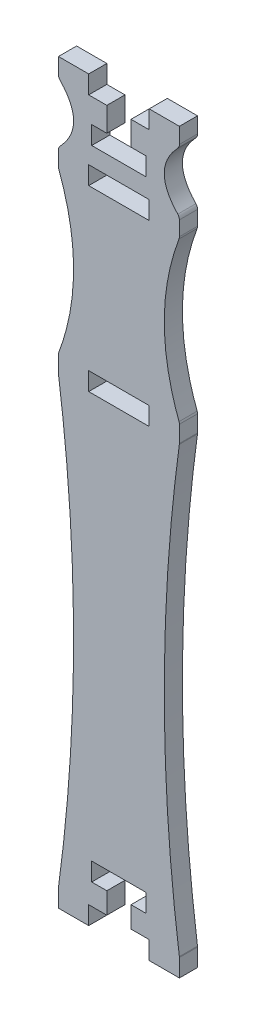
SolidWorks part; units mm, degrees
ref_plane "Alzado" through (0, 0, 0) normal (0, 0, 1) x (1, 0, 0)
ref_plane "Planta" through (0, 0, 0) normal (0, 1, 0) x (1, 0, 0)
ref_plane "Vista lateral" through (0, 0, 0) normal (1, 0, 0) x (0, 0, -1)
sketch "Croquis1" plane through (0, 0, 0) normal (0, 0, 1) x (1, 0, 0)
  line L1 (-10, 70) -> (-10, 67)
  line L2 (-7, 67) -> (-10, 67)
  line L4 (-15, 70) -> (-15, 67.4057)
  line L6 (-7, -45.5) -> (-7, -49)
  line L7 (-0.5, -42.5) -> (-9.5, -42.5)
  line L9 (-10, 70) -> (-15, 70)
  line L10 (-9.5, 60) -> (-0.5, 60)
  line L11 (-10, -52) -> (-10, -49)
  line L12 (-10, -52) -> (-15, -52)
  line L13 (-0.5, -42.5) -> (-0.5, -45.5)
  line L14 (-0.5, -45.5) -> (-3, -45.5)
  line L15 (-15, -52) -> (-15, -51.7014)
  line L16 (0, -49) -> (0, -52)
  line L17 (-0.5, 60) -> (-0.5, 63)
  line L18 (-3, -45.5) -> (-3, -49)
  line L19 (-0.5, 63) -> (-3, 63)
  line L20 (-10, 27.5) -> (-10, 24.5)
  line L21 (-3, 63) -> (-3, 67)
  line L22 (-10, 24.5) -> (0, 24.5)
  line L23 (0, 24.5) -> (0, 27.5)
  line L24 (-7, 63) -> (-7, 67)
  line L25 (-15, 27.3187) -> (-15, 24.5677)
  line L26 (-9.5, -45.5) -> (-7, -45.5)
  line L27 (-9.5, -42.5) -> (-9.5, -45.5)
  line L28 (-7, -49) -> (-10, -49)
  line L29 (-9.5, 63) -> (-7, 63)
  line L30 (-9.5, 60) -> (-9.5, 63)
  line L31 (-10, 54) -> (-10, 57)
  line L32 (-10, 54) -> (0, 54)
  line L33 (-10, 57) -> (0, 57)
  line L34 (0, 57) -> (0, 54)
  line L35 (-3, 67) -> (0, 67)
  line L36 (0, -52) -> (5, -52)
  line L37 (0, 67) -> (0, 70)
  line L38 (5, 70) -> (0, 70)
  line L39 (5, -52) -> (5, -51.7014)
  line L40 (0, 27.5) -> (-10, 27.5)
  line L42 (-15, 56.5943) -> (-15, 54.1813)
  line L43 (0, -49) -> (-3, -49)
  line L46 (-15, -49.0677) -> (-15, -51.7014)
  line L51 (5, -51.7014) -> (5, -49.0677)
  line L53 (5, 24.5677) -> (5, 27.3187)
  line L55 (5, 54.1813) -> (5, 56.5943)
  line L57 (5, 67.4057) -> (5, 70)
  arc A4 (-14.9909, -48.9331) -> (-15, -49.0677) centre (-14, -49.0677) ccw
  arc A5 (5, -49.0677) -> (4.9909, -48.9331) centre (4, -49.0677) ccw
  arc A6 (-15, 24.5677) -> (-14.9909, 24.4331) centre (-14, 24.5677) ccw
  arc A7 (4.9909, 24.4331) -> (5, 24.5677) centre (4, 24.5677) ccw
  arc A8 (-14.9371, 27.6678) -> (-15, 27.3187) centre (-14, 27.3187) ccw
  arc A9 (5, 27.3187) -> (4.9371, 27.6678) centre (4, 27.3187) ccw
  arc A10 (-14.7272, 57.2807) -> (-15, 56.5943) centre (-14, 56.5943) ccw
  arc A11 (-15, 54.1813) -> (-14.9371, 53.8322) centre (-14, 54.1813) ccw
  arc A12 (4.9371, 53.8322) -> (5, 54.1813) centre (4, 54.1813) ccw
  arc A13 (5, 56.5943) -> (4.7272, 57.2807) centre (4, 56.5943) ccw
  arc A14 (4.7272, 66.7193) -> (5, 67.4057) centre (4, 67.4057) ccw
  arc A15 (-15, 67.4057) -> (-14.7272, 66.7193) centre (-14, 67.4057) ccw
  spline S0 degree 3 poles (4.7272, 66.7193) (3.2424, 65.1462) (1.7576, 62) (3.2424, 58.8538) (4.7272, 57.2807) knots 0.028065 0.028065 0.028065 0.028065 0.5 0.971935 0.971935 0.971935 0.971935
  spline S1 degree 3 poles (-14.7272, 57.2807) (-13.2424, 58.8538) (-11.7576, 62) (-13.2424, 65.1462) (-14.7272, 66.7193) knots 0.028065 0.028065 0.028065 0.028065 0.5 0.971935 0.971935 0.971935 0.971935
  spline S2 degree 3 poles (-14.9371, 53.8322) (-13.3124, 49.4715) (-11.6876, 40.75) (-13.3124, 32.0285) (-14.9371, 27.6678) knots 0.006333 0.006333 0.006333 0.006333 0.5 0.993667 0.993667 0.993667 0.993667
  spline S3 degree 3 poles (4.9371, 53.8322) (3.3124, 49.4715) (1.6876, 40.75) (3.3124, 32.0285) (4.9371, 27.6678) knots 0.006333 0.006333 0.006333 0.006333 0.5 0.993667 0.993667 0.993667 0.993667
  spline S4 degree 3 poles (-14.9909, -48.9331) (-13.3303, -36.7054) (-11.6697, -12.25) (-13.3303, 12.2054) (-14.9909, 24.4331) knots 0.00091 0.00091 0.00091 0.00091 0.5 0.99909 0.99909 0.99909 0.99909
  spline S7 degree 3 poles (4.9909, -48.9331) (3.3303, -36.7054) (1.6697, -12.25) (3.3303, 12.2054) (4.9909, 24.4331) knots 0.00091 0.00091 0.00091 0.00091 0.5 0.99909 0.99909 0.99909 0.99909
extrude "Saliente-Extruir1" add sketch "Croquis1" along normal blind 3
